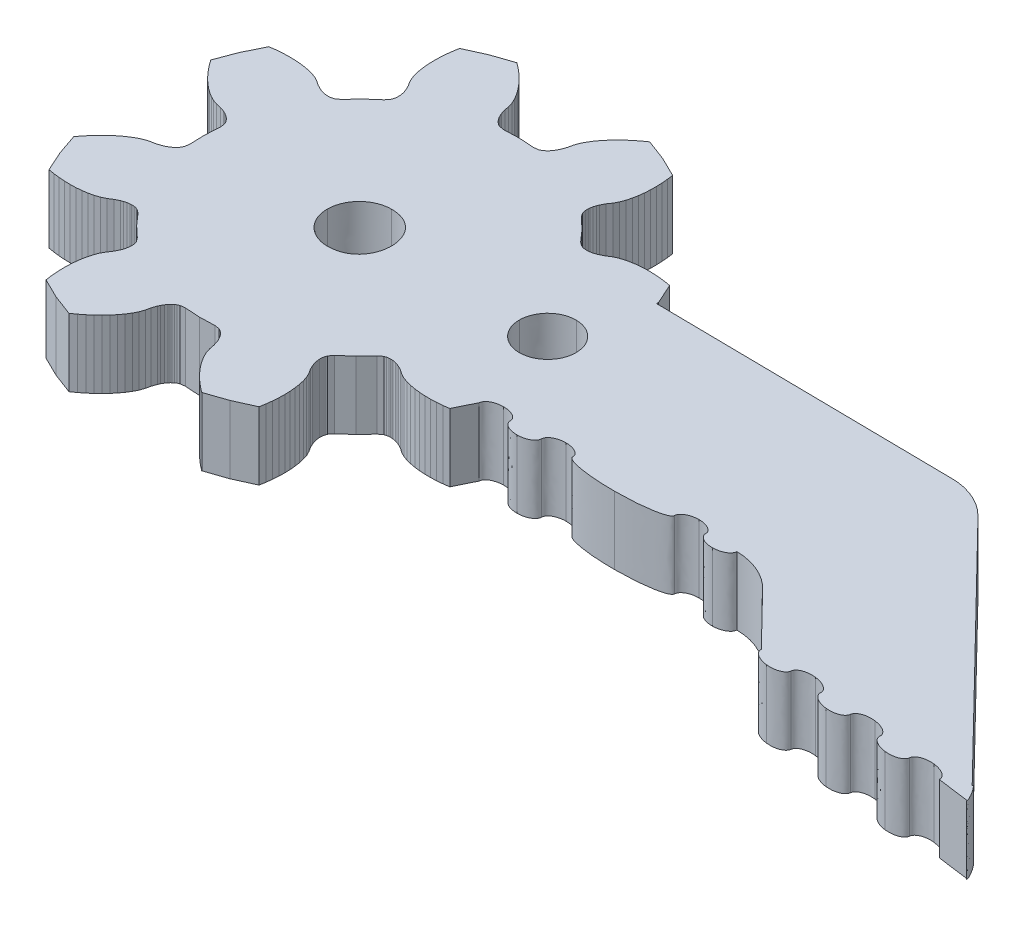
SolidWorks part; units mm, degrees
ref_plane "Front Plane" through (0, 0, 0) normal (0, 0, 1) x (1, 0, 0)
ref_plane "Top Plane" through (0, 0, 0) normal (0, 1, 0) x (1, 0, 0)
ref_plane "Right Plane" through (0, 0, 0) normal (1, 0, 0) x (0, 0, -1)
sketch "Sketch1" plane through (0, 0, 0) normal (0, 1, 0) x (1, 0, 0)
  line L1608 (118.5341, 166.0961) -> (118.5341, 166.193)
  line L1609 (118.5341, 166.193) -> (118.1081, 167.1345)
  line L1610 (118.1081, 167.1345) -> (117.8266, 167.1811)
  line L1611 (117.8266, 167.1811) -> (117.5494, 167.2141)
  line L1612 (117.5494, 167.2141) -> (117.277, 167.2336)
  line L1613 (117.277, 167.2336) -> (117.0101, 167.2392)
  line L1614 (117.0101, 167.2392) -> (116.7493, 167.2309)
  line L1615 (116.7493, 167.2309) -> (116.4956, 167.2082)
  line L1616 (116.4956, 167.2082) -> (116.2497, 167.1704)
  line L1617 (116.2497, 167.1704) -> (116.0133, 167.1164)
  line L1618 (116.0133, 167.1164) -> (115.7883, 167.0435)
  line L1619 (115.7883, 167.0435) -> (115.5824, 166.9415)
  line L1620 (115.5824, 166.9415) -> (115.3904, 166.8184)
  line L1621 (115.3904, 166.8184) -> (115.1836, 166.7174)
  line L1622 (115.1836, 166.7174) -> (115.0732, 166.6772)
  line L1623 (115.0732, 166.6772) -> (114.9567, 166.6456)
  line L1624 (114.9567, 166.6456) -> (114.8323, 166.6253)
  line L1625 (114.8323, 166.6253) -> (114.766, 166.6206)
  line L1626 (114.766, 166.6206) -> (114.696, 166.6208)
  line L1627 (114.696, 166.6208) -> (114.6211, 166.6276)
  line L1628 (114.6211, 166.6276) -> (114.5385, 166.6443)
  line L1629 (114.5385, 166.6443) -> (114.4416, 166.6792)
  line L1630 (114.4416, 166.6792) -> (114.2616, 166.8186)
  line L1631 (114.2616, 166.8186) -> (113.7953, 167.3484)
  line L1632 (113.7953, 167.3484) -> (113.2804, 167.8311)
  line L1633 (113.2804, 167.8311) -> (113.1468, 168.0154)
  line L1634 (113.1468, 168.0154) -> (113.1149, 168.1133)
  line L1635 (113.1149, 168.1133) -> (113.1008, 168.1964)
  line L1636 (113.1008, 168.1964) -> (113.0963, 168.2716)
  line L1637 (113.0963, 168.2716) -> (113.0983, 168.3415)
  line L1638 (113.0983, 168.3415) -> (113.1051, 168.4076)
  line L1639 (113.1051, 168.4076) -> (113.1293, 168.5313)
  line L1640 (113.1293, 168.5313) -> (113.1645, 168.6468)
  line L1641 (113.1645, 168.6468) -> (113.2082, 168.7559)
  line L1642 (113.2082, 168.7559) -> (113.3157, 168.9594)
  line L1643 (113.3157, 168.9594) -> (113.4447, 169.1474)
  line L1644 (113.4447, 169.1474) -> (113.5532, 169.35)
  line L1645 (113.5532, 169.35) -> (113.633, 169.5726)
  line L1646 (113.633, 169.5726) -> (113.6945, 169.8072)
  line L1647 (113.6945, 169.8072) -> (113.74, 170.0517)
  line L1648 (113.74, 170.0517) -> (113.7706, 170.3047)
  line L1649 (113.7706, 170.3047) -> (113.7871, 170.565)
  line L1650 (113.7871, 170.565) -> (113.7899, 170.832)
  line L1651 (113.7899, 170.832) -> (113.779, 171.1049)
  line L1652 (113.779, 171.1049) -> (113.7547, 171.383)
  line L1653 (113.7547, 171.383) -> (113.717, 171.6658)
  line L1654 (113.717, 171.6658) -> (112.7893, 172.1212)
  line L1655 (112.7893, 172.1212) -> (111.8223, 172.4857)
  line L1656 (111.8223, 172.4857) -> (111.5903, 172.3196)
  line L1657 (111.5903, 172.3196) -> (111.371, 172.1469)
  line L1658 (111.371, 172.1469) -> (111.1646, 171.9681)
  line L1659 (111.1646, 171.9681) -> (110.9718, 171.7833)
  line L1660 (110.9718, 171.7833) -> (110.7934, 171.593)
  line L1661 (110.7934, 171.593) -> (110.63, 171.3975)
  line L1662 (110.63, 171.3975) -> (110.4829, 171.197)
  line L1663 (110.4829, 171.197) -> (110.3539, 170.9916)
  line L1664 (110.3539, 170.9916) -> (110.2464, 170.781)
  line L1665 (110.2464, 170.781) -> (110.1728, 170.5633)
  line L1666 (110.1728, 170.5633) -> (110.1241, 170.3405)
  line L1667 (110.1241, 170.3405) -> (110.0493, 170.1228)
  line L1668 (110.0493, 170.1228) -> (109.9997, 170.0163)
  line L1669 (109.9997, 170.0163) -> (109.9397, 169.9116)
  line L1670 (109.9397, 169.9116) -> (109.8661, 169.8092)
  line L1671 (109.8661, 169.8092) -> (109.8225, 169.759)
  line L1672 (109.8225, 169.759) -> (109.7729, 169.7097)
  line L1673 (109.7729, 169.7097) -> (109.715, 169.6615)
  line L1674 (109.715, 169.6615) -> (109.6448, 169.615)
  line L1675 (109.6448, 169.615) -> (109.5516, 169.5712)
  line L1676 (109.5516, 169.5712) -> (109.3258, 169.5424)
  line L1677 (109.3258, 169.5424) -> (108.6215, 169.5873)
  line L1678 (108.6215, 169.5873) -> (107.9161, 169.5646)
  line L1679 (107.9161, 169.5646) -> (107.6912, 169.6004)
  line L1680 (107.6912, 169.6004) -> (107.5995, 169.6471)
  line L1681 (107.5995, 169.6471) -> (107.5307, 169.6959)
  line L1682 (107.5307, 169.6959) -> (107.4745, 169.7459)
  line L1683 (107.4745, 169.7459) -> (107.4264, 169.7967)
  line L1684 (107.4264, 169.7967) -> (107.3844, 169.8482)
  line L1685 (107.3844, 169.8482) -> (107.3141, 169.9529)
  line L1686 (107.3141, 169.9529) -> (107.2574, 170.0594)
  line L1687 (107.2574, 170.0594) -> (107.2111, 170.1674)
  line L1688 (107.2111, 170.1674) -> (107.1432, 170.3873)
  line L1689 (107.1432, 170.3873) -> (107.1015, 170.6115)
  line L1690 (107.1015, 170.6115) -> (107.0349, 170.8315)
  line L1691 (107.0349, 170.8315) -> (106.934, 171.0453)
  line L1692 (106.934, 171.0453) -> (106.8116, 171.2547)
  line L1693 (106.8116, 171.2547) -> (106.6708, 171.4597)
  line L1694 (106.6708, 171.4597) -> (106.5136, 171.6603)
  line L1695 (106.5136, 171.6603) -> (106.3412, 171.856)
  line L1696 (106.3412, 171.856) -> (106.1543, 172.0467)
  line L1697 (106.1543, 172.0467) -> (105.9537, 172.232)
  line L1698 (105.9537, 172.232) -> (105.7399, 172.4115)
  line L1699 (105.7399, 172.4115) -> (105.5133, 172.5848)
  line L1700 (105.5133, 172.5848) -> (104.5353, 172.2508)
  line L1701 (104.5353, 172.2508) -> (103.5937, 171.8248)
  line L1702 (103.5937, 171.8248) -> (103.5472, 171.5433)
  line L1703 (103.5472, 171.5433) -> (103.5141, 171.2661)
  line L1704 (103.5141, 171.2661) -> (103.4947, 170.9937)
  line L1705 (103.4947, 170.9937) -> (103.489, 170.7268)
  line L1706 (103.489, 170.7268) -> (103.4974, 170.4661)
  line L1707 (103.4974, 170.4661) -> (103.52, 170.2122)
  line L1708 (103.52, 170.2122) -> (103.5578, 169.9665)
  line L1709 (103.5578, 169.9665) -> (103.6119, 169.73)
  line L1710 (103.6119, 169.73) -> (103.6847, 169.5051)
  line L1711 (103.6847, 169.5051) -> (103.7867, 169.2991)
  line L1712 (103.7867, 169.2991) -> (103.9099, 169.1071)
  line L1713 (103.9099, 169.1071) -> (104.0108, 168.9003)
  line L1714 (104.0108, 168.9003) -> (104.0511, 168.7899)
  line L1715 (104.0511, 168.7899) -> (104.0826, 168.6735)
  line L1716 (104.0826, 168.6735) -> (104.103, 168.549)
  line L1717 (104.103, 168.549) -> (104.1077, 168.4827)
  line L1718 (104.1077, 168.4827) -> (104.1075, 168.4127)
  line L1719 (104.1075, 168.4127) -> (104.1006, 168.3378)
  line L1720 (104.1006, 168.3378) -> (104.0839, 168.2552)
  line L1721 (104.0839, 168.2552) -> (104.049, 168.1583)
  line L1722 (104.049, 168.1583) -> (103.9096, 167.9783)
  line L1723 (103.9096, 167.9783) -> (103.3799, 167.512)
  line L1724 (103.3799, 167.512) -> (102.8972, 166.9971)
  line L1725 (102.8972, 166.9971) -> (102.7129, 166.8635)
  line L1726 (102.7129, 166.8635) -> (102.6149, 166.8316)
  line L1727 (102.6149, 166.8316) -> (102.5318, 166.8175)
  line L1728 (102.5318, 166.8175) -> (102.4567, 166.8131)
  line L1729 (102.4567, 166.8131) -> (102.3868, 166.815)
  line L1730 (102.3868, 166.815) -> (102.3207, 166.8218)
  line L1731 (102.3207, 166.8218) -> (102.1969, 166.8461)
  line L1732 (102.1969, 166.8461) -> (102.0815, 166.8813)
  line L1733 (102.0815, 166.8813) -> (101.9724, 166.9249)
  line L1734 (101.9724, 166.9249) -> (101.7689, 167.0324)
  line L1735 (101.7689, 167.0324) -> (101.5809, 167.1615)
  line L1736 (101.5809, 167.1615) -> (101.3782, 167.2699)
  line L1737 (101.3782, 167.2699) -> (101.1557, 167.3498)
  line L1738 (101.1557, 167.3498) -> (100.921, 167.4112)
  line L1739 (100.921, 167.4112) -> (100.6765, 167.4567)
  line L1740 (100.6765, 167.4567) -> (100.4236, 167.4874)
  line L1741 (100.4236, 167.4874) -> (100.1632, 167.5039)
  line L1742 (100.1632, 167.5039) -> (99.8963, 167.5066)
  line L1743 (99.8963, 167.5066) -> (99.6234, 167.4957)
  line L1744 (99.6234, 167.4957) -> (99.3453, 167.4714)
  line L1745 (99.3453, 167.4714) -> (99.0625, 167.4337)
  line L1746 (99.0625, 167.4337) -> (98.6071, 166.506)
  line L1747 (98.6071, 166.506) -> (98.2426, 165.539)
  line L1748 (98.2426, 165.539) -> (98.4087, 165.3071)
  line L1749 (98.4087, 165.3071) -> (98.5813, 165.0877)
  line L1750 (98.5813, 165.0877) -> (98.7602, 164.8813)
  line L1751 (98.7602, 164.8813) -> (98.9449, 164.6886)
  line L1752 (98.9449, 164.6886) -> (99.1352, 164.5101)
  line L1753 (99.1352, 164.5101) -> (99.3307, 164.3467)
  line L1754 (99.3307, 164.3467) -> (99.5312, 164.1996)
  line L1755 (99.5312, 164.1996) -> (99.7367, 164.0706)
  line L1756 (99.7367, 164.0706) -> (99.9472, 163.9631)
  line L1757 (99.9472, 163.9631) -> (100.165, 163.8895)
  line L1758 (100.165, 163.8895) -> (100.3878, 163.8409)
  line L1759 (100.3878, 163.8409) -> (100.6054, 163.7661)
  line L1760 (100.6054, 163.7661) -> (100.7119, 163.7165)
  line L1761 (100.7119, 163.7165) -> (100.8166, 163.6564)
  line L1762 (100.8166, 163.6564) -> (100.919, 163.5828)
  line L1763 (100.919, 163.5828) -> (100.9692, 163.5392)
  line L1764 (100.9692, 163.5392) -> (101.0185, 163.4896)
  line L1765 (101.0185, 163.4896) -> (101.0667, 163.4318)
  line L1766 (101.0667, 163.4318) -> (101.1133, 163.3615)
  line L1767 (101.1133, 163.3615) -> (101.1571, 163.2683)
  line L1768 (101.1571, 163.2683) -> (101.1858, 163.0425)
  line L1769 (101.1858, 163.0425) -> (101.1409, 162.3382)
  line L1770 (101.1409, 162.3382) -> (101.1637, 161.6328)
  line L1771 (101.1637, 161.6328) -> (101.1279, 161.408)
  line L1772 (101.1279, 161.408) -> (101.0812, 161.3162)
  line L1773 (101.0812, 161.3162) -> (101.0324, 161.2475)
  line L1774 (101.0324, 161.2475) -> (100.9824, 161.1912)
  line L1775 (100.9824, 161.1912) -> (100.9316, 161.1431)
  line L1776 (100.9316, 161.1431) -> (100.88, 161.1012)
  line L1777 (100.88, 161.1012) -> (100.7753, 161.0308)
  line L1778 (100.7753, 161.0308) -> (100.6689, 160.9741)
  line L1779 (100.6689, 160.9741) -> (100.5608, 160.9278)
  line L1780 (100.5608, 160.9278) -> (100.341, 160.8599)
  line L1781 (100.341, 160.8599) -> (100.1167, 160.8183)
  line L1782 (100.1167, 160.8183) -> (99.8968, 160.7516)
  line L1783 (99.8968, 160.7516) -> (99.6829, 160.6507)
  line L1784 (99.6829, 160.6507) -> (99.4736, 160.5283)
  line L1785 (99.4736, 160.5283) -> (99.2685, 160.3876)
  line L1786 (99.2685, 160.3876) -> (99.068, 160.2304)
  line L1787 (99.068, 160.2304) -> (98.8722, 160.0579)
  line L1788 (98.8722, 160.0579) -> (98.6815, 159.8711)
  line L1789 (98.6815, 159.8711) -> (98.4962, 159.6704)
  line L1790 (98.4962, 159.6704) -> (98.3167, 159.4566)
  line L1791 (98.3167, 159.4566) -> (98.1435, 159.23)
  line L1792 (98.1435, 159.23) -> (98.4774, 158.252)
  line L1793 (98.4774, 158.252) -> (98.9034, 157.3104)
  line L1794 (98.9034, 157.3104) -> (99.1849, 157.2639)
  line L1795 (99.1849, 157.2639) -> (99.4621, 157.2308)
  line L1796 (99.4621, 157.2308) -> (99.7345, 157.2114)
  line L1797 (99.7345, 157.2114) -> (100.0015, 157.2058)
  line L1798 (100.0015, 157.2058) -> (100.2622, 157.2141)
  line L1799 (100.2622, 157.2141) -> (100.516, 157.2368)
  line L1800 (100.516, 157.2368) -> (100.7618, 157.2745)
  line L1801 (100.7618, 157.2745) -> (100.9983, 157.3286)
  line L1802 (100.9983, 157.3286) -> (101.2232, 157.4015)
  line L1803 (101.2232, 157.4015) -> (101.4292, 157.5035)
  line L1804 (101.4292, 157.5035) -> (101.6211, 157.6266)
  line L1805 (101.6211, 157.6266) -> (101.8279, 157.7276)
  line L1806 (101.8279, 157.7276) -> (101.9383, 157.7678)
  line L1807 (101.9383, 157.7678) -> (102.0548, 157.7994)
  line L1808 (102.0548, 157.7994) -> (102.1793, 157.8197)
  line L1809 (102.1793, 157.8197) -> (102.2455, 157.8244)
  line L1810 (102.2455, 157.8244) -> (102.3155, 157.8242)
  line L1811 (102.3155, 157.8242) -> (102.3905, 157.8174)
  line L1812 (102.3905, 157.8174) -> (102.4731, 157.8007)
  line L1813 (102.4731, 157.8007) -> (102.5699, 157.7657)
  line L1814 (102.5699, 157.7657) -> (102.7499, 157.6264)
  line L1815 (102.7499, 157.6264) -> (103.2163, 157.0966)
  line L1816 (103.2163, 157.0966) -> (103.7311, 156.6139)
  line L1817 (103.7311, 156.6139) -> (103.8648, 156.4296)
  line L1818 (103.8648, 156.4296) -> (103.8966, 156.3317)
  line L1819 (103.8966, 156.3317) -> (103.9107, 156.2486)
  line L1820 (103.9107, 156.2486) -> (103.9152, 156.1734)
  line L1821 (103.9152, 156.1734) -> (103.9132, 156.1035)
  line L1822 (103.9132, 156.1035) -> (103.9065, 156.0374)
  line L1823 (103.9065, 156.0374) -> (103.8822, 155.9136)
  line L1824 (103.8822, 155.9136) -> (103.847, 155.7982)
  line L1825 (103.847, 155.7982) -> (103.8033, 155.6891)
  line L1826 (103.8033, 155.6891) -> (103.6959, 155.4856)
  line L1827 (103.6959, 155.4856) -> (103.5668, 155.2976)
  line L1828 (103.5668, 155.2976) -> (103.4584, 155.0949)
  line L1829 (103.4584, 155.0949) -> (103.3785, 154.8724)
  line L1830 (103.3785, 154.8724) -> (103.317, 154.6378)
  line L1831 (103.317, 154.6378) -> (103.2715, 154.3933)
  line L1832 (103.2715, 154.3933) -> (103.2409, 154.1403)
  line L1833 (103.2409, 154.1403) -> (103.2244, 153.8799)
  line L1834 (103.2244, 153.8799) -> (103.2217, 153.613)
  line L1835 (103.2217, 153.613) -> (103.2325, 153.3401)
  line L1836 (103.2325, 153.3401) -> (103.2568, 153.062)
  line L1837 (103.2568, 153.062) -> (103.2945, 152.7792)
  line L1838 (103.2945, 152.7792) -> (104.2222, 152.3238)
  line L1839 (104.2222, 152.3238) -> (105.1892, 151.9593)
  line L1840 (105.1892, 151.9593) -> (105.4212, 152.1254)
  line L1841 (105.4212, 152.1254) -> (105.6406, 152.298)
  line L1842 (105.6406, 152.298) -> (105.8469, 152.4769)
  line L1843 (105.8469, 152.4769) -> (106.0397, 152.6617)
  line L1844 (106.0397, 152.6617) -> (106.2182, 152.8519)
  line L1845 (106.2182, 152.8519) -> (106.3816, 153.0474)
  line L1846 (106.3816, 153.0474) -> (106.5287, 153.248)
  line L1847 (106.5287, 153.248) -> (106.6576, 153.4534)
  line L1848 (106.6576, 153.4534) -> (106.7652, 153.6639)
  line L1849 (106.7652, 153.6639) -> (106.8387, 153.8817)
  line L1850 (106.8387, 153.8817) -> (106.8874, 154.1045)
  line L1851 (106.8874, 154.1045) -> (106.9622, 154.3221)
  line L1852 (106.9622, 154.3221) -> (107.0118, 154.4286)
  line L1853 (107.0118, 154.4286) -> (107.0719, 154.5333)
  line L1854 (107.0719, 154.5333) -> (107.1455, 154.6358)
  line L1855 (107.1455, 154.6358) -> (107.189, 154.6859)
  line L1856 (107.189, 154.6859) -> (107.2386, 154.7352)
  line L1857 (107.2386, 154.7352) -> (107.2965, 154.7834)
  line L1858 (107.2965, 154.7834) -> (107.3667, 154.83)
  line L1859 (107.3667, 154.83) -> (107.4599, 154.8738)
  line L1860 (107.4599, 154.8738) -> (107.6857, 154.9026)
  line L1861 (107.6857, 154.9026) -> (108.3901, 154.8577)
  line L1862 (108.3901, 154.8577) -> (109.0955, 154.8804)
  line L1863 (109.0955, 154.8804) -> (109.3203, 154.8446)
  line L1864 (109.3203, 154.8446) -> (109.4121, 154.7979)
  line L1865 (109.4121, 154.7979) -> (109.4808, 154.7491)
  line L1866 (109.4808, 154.7491) -> (109.5371, 154.6991)
  line L1867 (109.5371, 154.6991) -> (109.5851, 154.6483)
  line L1868 (109.5851, 154.6483) -> (109.6271, 154.5968)
  line L1869 (109.6271, 154.5968) -> (109.6974, 154.4921)
  line L1870 (109.6974, 154.4921) -> (109.7542, 154.3856)
  line L1871 (109.7542, 154.3856) -> (109.8004, 154.2775)
  line L1872 (109.8004, 154.2775) -> (109.8684, 154.0577)
  line L1873 (109.8684, 154.0577) -> (109.91, 153.8335)
  line L1874 (109.91, 153.8335) -> (109.9767, 153.6135)
  line L1875 (109.9767, 153.6135) -> (110.0775, 153.3997)
  line L1876 (110.0775, 153.3997) -> (110.2, 153.1903)
  line L1877 (110.2, 153.1903) -> (110.3407, 152.9852)
  line L1878 (110.3407, 152.9852) -> (110.4979, 152.7847)
  line L1879 (110.4979, 152.7847) -> (110.6703, 152.5889)
  line L1880 (110.6703, 152.5889) -> (110.8572, 152.3982)
  line L1881 (110.8572, 152.3982) -> (111.0578, 152.213)
  line L1882 (111.0578, 152.213) -> (111.2717, 152.0335)
  line L1883 (111.2717, 152.0335) -> (111.4983, 151.8602)
  line L1884 (111.4983, 151.8602) -> (112.4763, 152.1941)
  line L1885 (112.4763, 152.1941) -> (113.4178, 152.6202)
  line L1886 (113.4178, 152.6202) -> (113.4644, 152.9016)
  line L1887 (113.4644, 152.9016) -> (113.4974, 153.1789)
  line L1888 (113.4974, 153.1789) -> (113.5168, 153.4513)
  line L1889 (113.5168, 153.4513) -> (113.5225, 153.7182)
  line L1890 (113.5225, 153.7182) -> (113.5142, 153.9789)
  line L1891 (113.5142, 153.9789) -> (113.4915, 154.2327)
  line L1892 (113.4915, 154.2327) -> (113.4537, 154.4785)
  line L1893 (113.4537, 154.4785) -> (113.3996, 154.715)
  line L1894 (113.3996, 154.715) -> (113.3268, 154.9399)
  line L1895 (113.3268, 154.9399) -> (113.2248, 155.1459)
  line L1896 (113.2248, 155.1459) -> (113.1017, 155.3378)
  line L1897 (113.1017, 155.3378) -> (113.0007, 155.5446)
  line L1898 (113.0007, 155.5446) -> (112.9604, 155.655)
  line L1899 (112.9604, 155.655) -> (112.9289, 155.7715)
  line L1900 (112.9289, 155.7715) -> (112.9085, 155.896)
  line L1901 (112.9085, 155.896) -> (112.9038, 155.9623)
  line L1902 (112.9038, 155.9623) -> (112.9041, 156.0322)
  line L1903 (112.9041, 156.0322) -> (112.9109, 156.1072)
  line L1904 (112.9109, 156.1072) -> (112.9276, 156.1898)
  line L1905 (112.9276, 156.1898) -> (112.9625, 156.2866)
  line L1906 (112.9625, 156.2866) -> (113.1019, 156.4667)
  line L1907 (113.1019, 156.4667) -> (113.6316, 156.933)
  line L1908 (113.6316, 156.933) -> (114.1144, 157.4478)
  line L1909 (114.1144, 157.4478) -> (114.2987, 157.5815)
  line L1910 (114.2987, 157.5815) -> (114.3966, 157.6133)
  line L1911 (114.3966, 157.6133) -> (114.4797, 157.6275)
  line L1912 (114.4797, 157.6275) -> (114.5548, 157.6319)
  line L1913 (114.5548, 157.6319) -> (114.6247, 157.63)
  line L1914 (114.6247, 157.63) -> (114.6908, 157.6232)
  line L1915 (114.6908, 157.6232) -> (114.8146, 157.5989)
  line L1916 (114.8146, 157.5989) -> (114.9301, 157.5637)
  line L1917 (114.9301, 157.5637) -> (115.0392, 157.52)
  line L1918 (115.0392, 157.52) -> (115.2426, 157.4126)
  line L1919 (115.2426, 157.4126) -> (115.4307, 157.2835)
  line L1920 (115.4307, 157.2835) -> (115.6333, 157.1751)
  line L1921 (115.6333, 157.1751) -> (115.8558, 157.0952)
  line L1922 (115.8558, 157.0952) -> (116.0905, 157.0337)
  line L1923 (116.0905, 157.0337) -> (116.335, 156.9883)
  line L1924 (116.335, 156.9883) -> (116.5879, 156.9576)
  line L1925 (116.5879, 156.9576) -> (116.8483, 156.9411)
  line L1926 (116.8483, 156.9411) -> (117.1153, 156.9384)
  line L1927 (117.1153, 156.9384) -> (117.3881, 156.9492)
  line L1928 (117.3881, 156.9492) -> (117.6663, 156.9736)
  line L1929 (117.6663, 156.9736) -> (117.949, 157.0112)
  line L1930 (117.949, 157.0112) -> (118.4045, 157.9389)
  line L1931 (118.4045, 157.9389) -> (118.4045, 157.9258)
  line L1932 (132.5703, 157.0207) -> (134.9881, 154.5418)
  line L1933 (144.4235, 153.4315) -> (145.928, 153.229)
  line L1934 (145.928, 153.229) -> (145.9277, 153.2017)
  line L1935 (145.4781, 153.975) -> (145.432, 153.9612)
  line L1936 (145.432, 153.9612) -> (134.6699, 164.9951)
  line L1937 (134.6699, 164.9951) -> (134.6664, 164.9966)
  line L1938 (132.5614, 165.9138) -> (118.5341, 166.0961)
  spline S1768 degree 3 poles (108.5161, 163.7225) (107.682, 163.7225) (107.006, 163.0508) (107.006, 162.2225) knots 0 0 0 0 0.25 0.25 0.25 0.25
  spline S1769 degree 3 poles (107.006, 162.2225) (107.0059, 161.394) (107.682, 160.7225) (108.516, 160.7225) knots 0.25 0.25 0.25 0.25 0.5 0.5 0.5 0.5
  spline S1770 degree 3 poles (108.516, 160.7225) (110.5024, 160.7225) (110.5023, 163.7225) (108.5161, 163.7225) knots 0.5 0.5 0.5 0.5 1 1 1 1
  spline S1771 degree 3 poles (118.6402, 162.206) (118.6493, 162.9376) (118.0635, 163.5382) (117.3319, 163.5473) knots 0 0 0 0 0.2 0.2 0.2 0.2
  spline S1772 degree 3 poles (117.3319, 163.5473) (116.6002, 163.5564) (115.9997, 162.9707) (115.9906, 162.2391) knots 0.2 0.2 0.2 0.2 0.4 0.4 0.4 0.4
  spline S1773 degree 3 poles (115.9906, 162.2391) (115.9813, 161.5073) (116.5672, 160.9069) (117.2988, 160.8978) knots 0.4 0.4 0.4 0.4 0.6 0.6 0.6 0.6
  spline S1774 degree 3 poles (117.2988, 160.8978) (118.0305, 160.8887) (118.631, 161.4743) (118.6402, 162.206) knots 0.6 0.6 0.6 0.6 1 1 1 1
  spline S1775 degree 3 poles (118.4045, 157.9258) (118.4077, 158.1539) (118.737, 158.3388) (119.1399, 158.3388) knots 0.902507 0.902507 0.902507 0.902507 0.905292 0.905292 0.905292 0.905292
  spline S1776 degree 3 poles (119.1399, 158.3388) (119.5429, 158.3388) (119.8669, 158.1539) (119.8638, 157.9258) knots 0.905292 0.905292 0.905292 0.905292 0.908078 0.908078 0.908078 0.908078
  spline S1777 degree 3 poles (119.8638, 157.9258) (119.8606, 157.6977) (120.1846, 157.5128) (120.5876, 157.5128) knots 0.908078 0.908078 0.908078 0.908078 0.910864 0.910864 0.910864 0.910864
  spline S1778 degree 3 poles (120.5876, 157.5128) (120.9905, 157.5128) (121.3198, 157.6977) (121.3231, 157.9258) knots 0.910864 0.910864 0.910864 0.910864 0.913649 0.913649 0.913649 0.913649
  spline S1779 degree 3 poles (121.3231, 157.9258) (121.3263, 158.1539) (121.6555, 158.3388) (122.0585, 158.3388) knots 0.913649 0.913649 0.913649 0.913649 0.916435 0.916435 0.916435 0.916435
  spline S1780 degree 3 poles (122.0585, 158.3388) (122.4614, 158.3388) (122.7855, 158.1539) (122.7825, 157.9258) knots 0.916435 0.916435 0.916435 0.916435 0.91922 0.91922 0.91922 0.91922
  spline S1781 degree 3 poles (122.7825, 157.9258) (122.7722, 157.6976) (123.8291, 157.5127) (125.1432, 157.5127) knots 0.91922 0.91922 0.91922 0.91922 0.922006 0.922006 0.922006 0.922006
  spline S1782 degree 3 poles (125.1432, 157.5127) (126.4573, 157.5127) (127.5311, 157.6976) (127.5416, 157.9258) knots 0.922006 0.922006 0.922006 0.922006 0.924791 0.924791 0.924791 0.924791
  spline S1783 degree 3 poles (127.5416, 157.9258) (127.5448, 158.1538) (127.874, 158.3387) (128.277, 158.3387) knots 0.924791 0.924791 0.924791 0.924791 0.927577 0.927577 0.927577 0.927577
  spline S1784 degree 3 poles (128.277, 158.3387) (128.6799, 158.3387) (129.004, 158.1538) (129.0008, 157.9257) knots 0.927577 0.927577 0.927577 0.927577 0.930362 0.930362 0.930362 0.930362
  spline S1785 degree 3 poles (129.0008, 157.9257) (128.9976, 157.6976) (129.3217, 157.5127) (129.7246, 157.5127) knots 0.930362 0.930362 0.930362 0.930362 0.933148 0.933148 0.933148 0.933148
  spline S1786 degree 3 poles (129.7246, 157.5127) (130.1276, 157.5127) (130.4568, 157.6976) (130.46, 157.9257) knots 0.933148 0.933148 0.933148 0.933148 0.935933 0.935933 0.935933 0.935933
  spline S1787 degree 3 poles (130.46, 157.9257) (131.2556, 157.9158) (132.0147, 157.5902) (132.5703, 157.0207) knots 0.935933 0.935933 0.935933 0.935933 0.938719 0.938719 0.938719 0.938719
  spline S1788 degree 3 poles (134.9881, 154.5418) (134.9649, 154.3148) (135.2981, 154.0895) (135.7323, 154.0383) knots 0.941504 0.941504 0.941504 0.941504 0.94429 0.94429 0.94429 0.94429
  spline S1789 degree 3 poles (135.7323, 154.0383) (136.1666, 153.9872) (136.5374, 154.1298) (136.5607, 154.3567) knots 0.94429 0.94429 0.94429 0.94429 0.947075 0.947075 0.947075 0.947075
  spline S1790 degree 3 poles (136.5607, 154.3567) (136.5839, 154.5837) (136.9547, 154.7262) (137.3889, 154.6751) knots 0.947075 0.947075 0.947075 0.947075 0.949861 0.949861 0.949861 0.949861
  spline S1791 degree 3 poles (137.3889, 154.6751) (137.8232, 154.624) (138.1564, 154.3986) (138.1333, 154.1717) knots 0.949861 0.949861 0.949861 0.949861 0.952646 0.952646 0.952646 0.952646
  spline S1792 degree 3 poles (138.1333, 154.1717) (138.11, 153.9448) (138.4432, 153.7194) (138.8775, 153.6683) knots 0.952646 0.952646 0.952646 0.952646 0.955432 0.955432 0.955432 0.955432
  spline S1793 degree 3 poles (138.8775, 153.6683) (139.3117, 153.6172) (139.6826, 153.7597) (139.7058, 153.9867) knots 0.955432 0.955432 0.955432 0.955432 0.958217 0.958217 0.958217 0.958217
  spline S1794 degree 3 poles (139.7058, 153.9867) (139.729, 154.2136) (140.0999, 154.3561) (140.5341, 154.305) knots 0.958217 0.958217 0.958217 0.958217 0.961003 0.961003 0.961003 0.961003
  spline S1795 degree 3 poles (140.5341, 154.305) (140.9684, 154.2539) (141.3016, 154.0285) (141.2784, 153.8016) knots 0.961003 0.961003 0.961003 0.961003 0.963788 0.963788 0.963788 0.963788
  spline S1796 degree 3 poles (141.2784, 153.8016) (141.2552, 153.5747) (141.5884, 153.3493) (142.0227, 153.2982) knots 0.963788 0.963788 0.963788 0.963788 0.966574 0.966574 0.966574 0.966574
  spline S1797 degree 3 poles (142.0227, 153.2982) (142.4569, 153.2471) (142.8277, 153.3896) (142.851, 153.6166) knots 0.966574 0.966574 0.966574 0.966574 0.969359 0.969359 0.969359 0.969359
  spline S1798 degree 3 poles (142.851, 153.6166) (142.8742, 153.8435) (143.245, 153.9861) (143.6793, 153.935) knots 0.969359 0.969359 0.969359 0.969359 0.972145 0.972145 0.972145 0.972145
  spline S1799 degree 3 poles (143.6793, 153.935) (144.1135, 153.8838) (144.4467, 153.6585) (144.4235, 153.4315) knots 0.972145 0.972145 0.972145 0.972145 0.97493 0.97493 0.97493 0.97493
  spline S1800 degree 3 poles (145.9277, 153.2017) (145.9948, 153.2009) (145.7107, 153.7365) (145.4781, 153.975) knots 0.980501 0.980501 0.980501 0.980501 0.983287 0.983287 0.983287 0.983287
  spline S1801 degree 3 poles (134.6664, 164.9966) (134.1141, 165.5694) (133.3569, 165.8993) (132.5614, 165.9138) knots 0.991643 0.991643 0.991643 0.991643 0.994429 0.994429 0.994429 0.994429
extrude "Boss-Extrude1" add sketch "Sketch1" along normal blind 3.175
